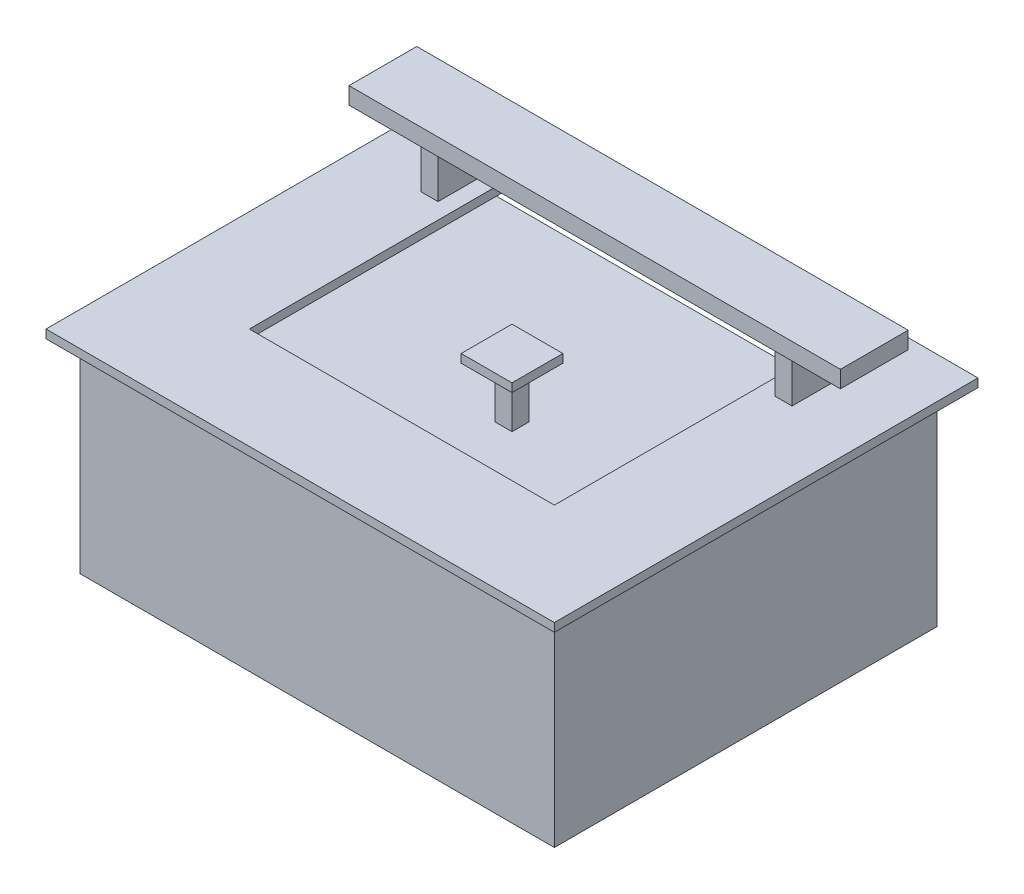
SolidWorks part; units mm, degrees
ref_plane "Front Plane" through (0, 0, 0) normal (0, 0, 1) x (1, 0, 0)
ref_plane "Top Plane" through (0, 0, 0) normal (0, 1, 0) x (1, 0, 0)
ref_plane "Right Plane" through (0, 0, 0) normal (1, 0, 0) x (0, 0, -1)
sketch "Sketch1" plane through (0, 0, 0) normal (0, 1, 0) x (1, 0, 0)
  line L0 (-900, 1250) -> (-900, -650)
  line L1 (-1500, 1250) -> (-900, 1250)
  line L2 (-1500, 1250) -> (-1500, -1250)
  line L3 (-1500, -1250) -> (1500, -1250)
  line L4 (1500, 1250) -> (1500, -1250)
  line L7 (-900, -650) -> (900, -650)
  line L8 (900, -650) -> (900, 1250)
  line L9 (900, 1250) -> (1500, 1250)
  line L11 (150, -150) -> (-150, -150)
  line L12 (150, -150) -> (150, 150)
  line L13 (150, 150) -> (-150, 150)
  line L14 (-150, -150) -> (-150, 150)
  line L15 (150, -150) -> (-150, 150) construction
  line L16 (150, 150) -> (-150, -150) construction
  point P0 (0, 0)
  point P8 (0, 0)
  point P15 (-2279.7054, -2037.4924)
  dimension "D1" = 3000
  dimension "D2" = 2500
  dimension "D3" = 600
  dimension "D4" = 600
  dimension "D5" = 600
  dimension "D6" = 300
  dimension "D7" = 300
  dimension "D8" = 650
extrude "Boss-Extrude1" add sketch "Sketch1" against normal blind 50
sketch "Sketch2" plane through (0, -50, 0) normal (0, -1, 0) x (1, 0, 0)
  line L0 (-1500, -1250) -> (-1500, 1250) construction
  line L1 (-1400, 1150) -> (1400, 1150)
  line L2 (-1400, 1150) -> (-1400, 1050)
  line L3 (-1300, 1050) -> (1300, 1050)
  line L4 (1400, 1150) -> (1400, 1050)
  line L6 (1300, 1050) -> (1300, -1107.8638)
  line L7 (1300, -1107.8638) -> (1400, -1107.8638)
  line L8 (1400, 1050) -> (1400, -1107.8638)
  line L10 (-1400, 1050) -> (-1400, -1107.8638)
  line L11 (-1400, -1107.8638) -> (-1300, -1107.8638)
  line L12 (-1300, 1050) -> (-1300, -1107.8638)
  line L13 (1500, 1250) -> (1500, -1250) construction
  line L14 (-1500, 1250) -> (1500, 1250) construction
  line L16 (50, -50) -> (-50, -50)
  line L17 (50, -50) -> (50, 50)
  line L18 (50, 50) -> (-50, 50)
  line L19 (-50, -50) -> (-50, 50)
  line L20 (50, -50) -> (-50, 50) construction
  line L21 (50, 50) -> (-50, -50) construction
  line L22 (-150, -150) -> (-150, 150) construction
  line L23 (-150, 0) -> (150, 0) construction
  line L24 (150, 150) -> (150, -150) construction
  line L25 (0, 150) -> (0, -150) construction
  line L26 (-150, 150) -> (150, 150) construction
  line L27 (150, -150) -> (-150, -150) construction
  point P16 (0, 0)
  point P33 (0, 0)
  dimension "D1" = 100
  dimension "D2" = 100
  dimension "D3" = 100
  dimension "D4" = 100
  dimension "D5" = 100
  dimension "D6" = 100
  dimension "D7" = 100
  dimension "D8" = 100
extrude "Boss-Extrude2" add sketch "Sketch2" along normal blind 1200
sketch "Sketch3" plane through (0, 0, 1050) normal (0, 0, -1) x (-1, 0, 0)
  line L0 (1300, -1250) -> (1300, -50) construction
  line L1 (-1300, -350) -> (1300, -350)
  line L2 (-1300, -350) -> (-1300, -450)
  line L3 (-1300, -450) -> (1300, -450)
  line L4 (1300, -350) -> (1300, -450)
  line L5 (-1300, -1250) -> (-1300, -50) construction
  line L6 (1300, -50) -> (-1300, -50) construction
  dimension "D1" = 100
  dimension "D2" = 300
extrude "Boss-Extrude3" add sketch "Sketch3" along normal up to surface (2157.8638 mm away) up to face at (-1350, -650, -1107.8638)
sketch "Sketch4" plane through (0, 0, 0) normal (0, 1, 0) x (1, 0, 0)
  line L0 (-994.2451, 688.0562) -> (994.2451, 688.0562) construction
  line L1 (994.2451, 818.4142) -> (1094.9973, 818.4142)
  line L2 (994.2451, 818.4142) -> (994.2451, 557.6983)
  line L3 (994.2451, 557.6983) -> (1094.9973, 557.6983)
  line L4 (1094.9973, 818.4142) -> (1094.9973, 557.6983)
  line L5 (-1094.9973, 818.4142) -> (-994.2451, 818.4142)
  line L6 (-1094.9973, 818.4142) -> (-1094.9973, 557.6983)
  line L7 (-1094.9973, 557.6983) -> (-994.2451, 557.6983)
  line L8 (-994.2451, 818.4142) -> (-994.2451, 557.6983)
  point P10 (0, 688.0562)
extrude "Boss-Extrude4" add sketch "Sketch4" along normal blind 300
sketch "Sketch5" plane through (0, 300, 0) normal (0, 1, 0) x (1, 0, 0)
  line L0 (150, 150) -> (-150, 150) construction
  line L1 (-1450, 888.0562) -> (1450, 888.0562)
  line L2 (-1450, 888.0562) -> (-1450, 488.0562)
  line L3 (-1450, 488.0562) -> (1450, 488.0562)
  line L4 (1450, 888.0562) -> (1450, 488.0562)
  line L5 (1094.9973, 557.6983) -> (1094.9973, 818.4142) construction
  point P4 (0, 488.0562)
  point P7 (0, 150)
  point P8 (1450, 688.0562)
  point P11 (1094.9973, 688.0562)
  dimension "D1" = 400
  dimension "D2" = 2900
extrude "Boss-Extrude5" add sketch "Sketch5" along normal blind 100
